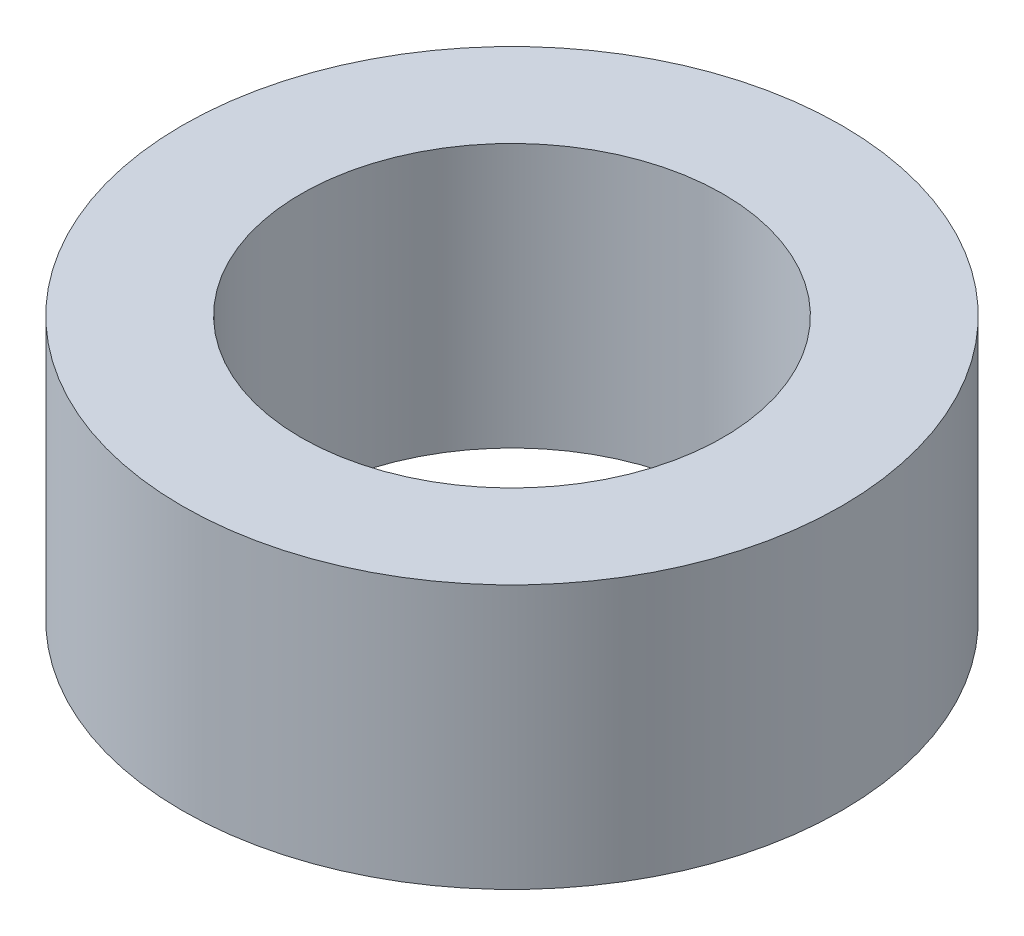
SolidWorks part; units mm, degrees
material "ABS"
ref_plane "Front Plane" through (0, 0, 0) normal (0, 0, 1) x (1, 0, 0)
ref_plane "Top Plane" through (0, 0, 0) normal (0, 1, 0) x (1, 0, 0)
ref_plane "Right Plane" through (0, 0, 0) normal (1, 0, 0) x (0, 0, -1)
sketch "Sketch1" plane through (0, 0, 0) normal (0, 1, 0) x (1, 0, 0)
  circle A0 centre (0, 0) radius 25
  dimension "D1" = 50
extrude "Boss-Extrude1" add sketch "Sketch1" along normal blind 20
sketch "Sketch2" plane through (0, 20, 0) normal (0, 1, 0) x (1, 0, 0)
  circle A0 centre (0, 0) radius 16
  dimension "D1" = 32
extrude "Cut-Extrude1" cut sketch "Sketch2" against normal through all
